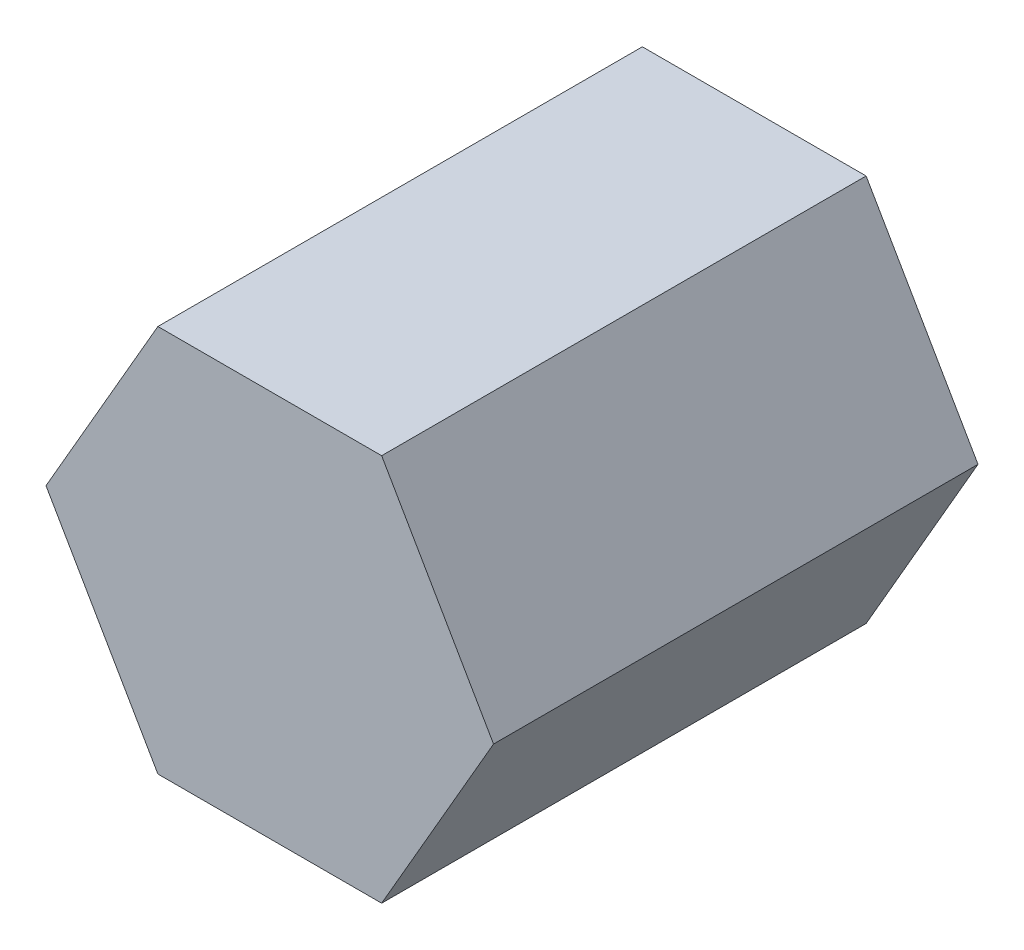
SolidWorks part; units mm, degrees
ref_plane "Front Plane" through (0, 0, 0) normal (0, 0, 1) x (1, 0, 0)
ref_plane "Top Plane" through (0, 0, 0) normal (0, 1, 0) x (1, 0, 0)
ref_plane "Right Plane" through (0, 0, 0) normal (1, 0, 0) x (0, 0, -1)
sketch "Sketch1" plane through (0, 0, 0) normal (0, 0, 1) x (1, 0, 0)
  line L1 (4.6188, 0) -> (2.3094, 4)
  line L2 (2.3094, 4) -> (-2.3094, 4)
  line L3 (-2.3094, 4) -> (-4.6188, 0)
  line L4 (-4.6188, 0) -> (-2.3094, -4)
  line L5 (-2.3094, -4) -> (2.3094, -4)
  line L6 (2.3094, -4) -> (4.6188, 0)
  circle A0 centre (0, 0) radius 4 construction
  dimension "D1" = 8
extrude "Boss-Extrude1" add sketch "Sketch1" along normal blind 10
sketch "Sketch2" plane through (0, 0, 0) normal (0, 0, -1) x (-1, 0, 0)
  line L0 (-1.11, 1.0457) -> (1.11, 1.0457)
  arc A0 (-1.11, 1.0457) -> (1.11, 1.0457) centre (0, 0) ccw
  dimension "D1" = 3.05
  dimension "D2" = 2.22
extrude "Cut-Extrude1" cut sketch "Sketch2" against normal blind 9 contours L0 A0
